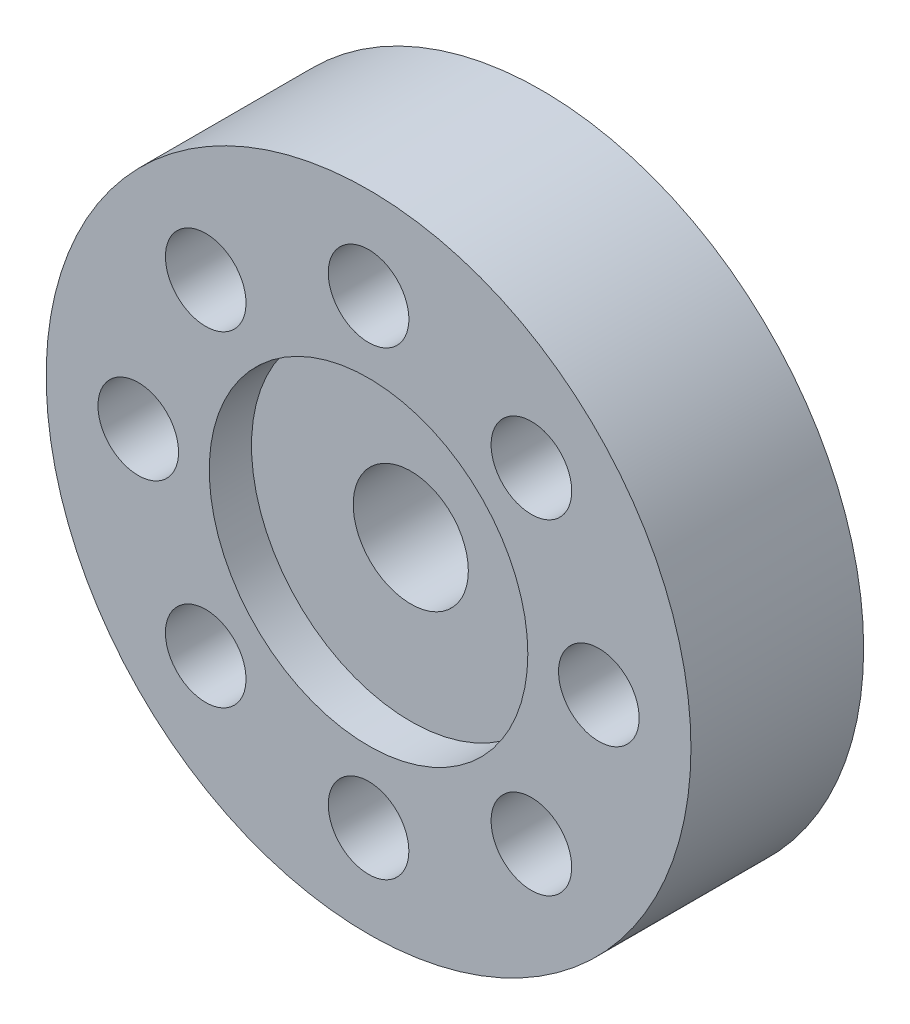
SolidWorks part; units mm, degrees
material "ABS"
ref_plane "正面" through (0, 0, 0) normal (0, 0, 1) x (1, 0, 0)
ref_plane "平面" through (0, 0, 0) normal (0, 1, 0) x (1, 0, 0)
ref_plane "右側面" through (0, 0, 0) normal (1, 0, 0) x (0, 0, -1)
sketch "ｽｹｯﾁ2" plane through (0, 0, 0) normal (0, 1, 0) x (1, 0, 0)
  line L0 (0, 0) -> (3.9, 0)
  line L1 (3.9, 0) -> (3.9, -0.8)
  line L2 (3.9, -0.8) -> (8.4, -0.8)
  line L3 (8.4, -0.8) -> (8.4, -5.3)
  line L4 (8.4, -5.3) -> (4.15, -5.3)
  line L5 (4.15, -5.3) -> (4.15, -4.2)
  line L6 (4.15, -4.2) -> (0, -4.2)
  line L7 (0, -4.2) -> (0, 0)
  line L8 (1.5, 0) -> (1.5, -4.2)
  dimension "D1" = 3.9
  dimension "D2" = 8.4
  dimension "D3" = 4.5
  dimension "D4" = 0.8
  dimension "D5" = 1.1
  dimension "D6" = 4.15
  dimension "D7" = 1.5
revolve "回転1" add sketch "ｽｹｯﾁ2" angle 360 about L7
sketch "ｽｹｯﾁ3" plane through (0, 0, 0.8) normal (0, 0, -1) x (-1, 0, 0)
  line L0 (0, 0) -> (0, 6) construction
  circle A0 centre (0, 6) radius 1.05
  dimension "D2" = 2.1
  dimension "D1" = 6
extrude "ｶｯﾄ - 押し出し1" cut sketch "ｽｹｯﾁ3" against normal through all
pattern_circular "円形ﾊﾟﾀｰﾝ1" count 8 over 360 about axis through (0, 0, 0) along (0, 0, 1) of "ｶｯﾄ - 押し出し1"
